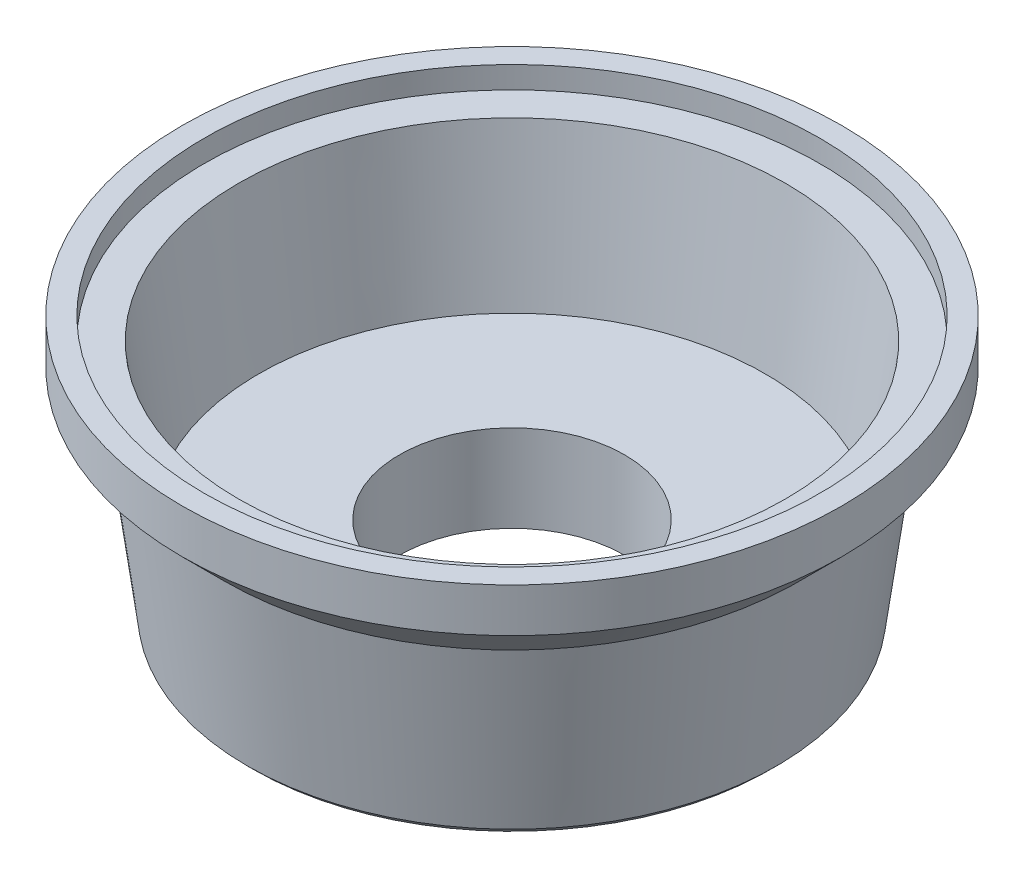
SolidWorks part; units mm, degrees
material "PLA"
ref_plane "Front Plane" through (0, 0, 0) normal (0, 0, 1) x (1, 0, 0)
ref_plane "Top Plane" through (0, 0, 0) normal (0, 1, 0) x (1, 0, 0)
ref_plane "Right Plane" through (0, 0, 0) normal (1, 0, 0) x (0, 0, -1)
sketch "Sketch1" plane through (0, 0, 0) normal (1, 0, 0) x (0, 0, -1)
  line L0 (0, 0) -> (0, -23.584) construction
  line L1 (0, 0) -> (38.1, 0)
  line L2 (38.1, 0) -> (42.2889, 31.75)
  line L3 (42.2889, 31.75) -> (47.625, 31.75)
  line L4 (47.625, 31.75) -> (47.625, 38.1)
  line L5 (47.625, 38.1) -> (0, 38.1)
  line L6 (0, 38.1) -> (0, 0)
  dimension "D1" = 76.2
  dimension "D2" = 95.25
  dimension "D3" = 6.35
  dimension "D4" = 38.1
revolve "Revolve2" add sketch "Sketch1" angle 360 about L0
shell "Shell1" thickness 3.175
sketch "Sketch2" plane through (0, 0, 0) normal (0, 0, 1) x (1, 0, 0)
  line L0 (0, 0) -> (0, -9.9308) construction
  line L1 (-37.2773, 12.5719) -> (0, 12.5719)
  line L2 (0, 12.5719) -> (0, 1.8888)
  line L3 (0, 1.8888) -> (-36.3681, 1.8888)
  line L4 (-36.3681, 1.8888) -> (-37.2773, 12.5719)
revolve "Revolve3" add sketch "Sketch2" angle 360 about L0
sketch "Sketch3" plane through (0, 12.5719, 0) normal (0, 1, 0) x (1, 0, 0)
  circle A0 centre (0, 0) radius 16.2712
  dimension "D1" = 32.5425
extrude "Cut-Extrude1" cut sketch "Sketch3" against normal through all
shell "Shell3" thickness 3.175
sketch "Sketch4" plane through (0, 0, 0) normal (0, 0, 1) x (1, 0, 0)
  line L0 (-47.625, 31.75) -> (-40.729, 24.854)
  line L1 (-47.625, 31.75) -> (47.625, 31.75) construction
  line L2 (-40.729, 24.854) -> (-40.729, 32.3551)
  line L3 (-40.729, 32.3551) -> (-47.625, 32.3551)
  line L4 (-47.625, 32.3551) -> (-47.625, 31.75)
  dimension "D1" = 45
revolve "Revolve4" add sketch "Sketch4" angle 360 about axis through (0, 0, 0) along (0, 1, 0)
chamfer "Chamfer1" distance 0.762 angle 45 2 edges at (0, 0, 38.1) (0, 0, 19.4462)
